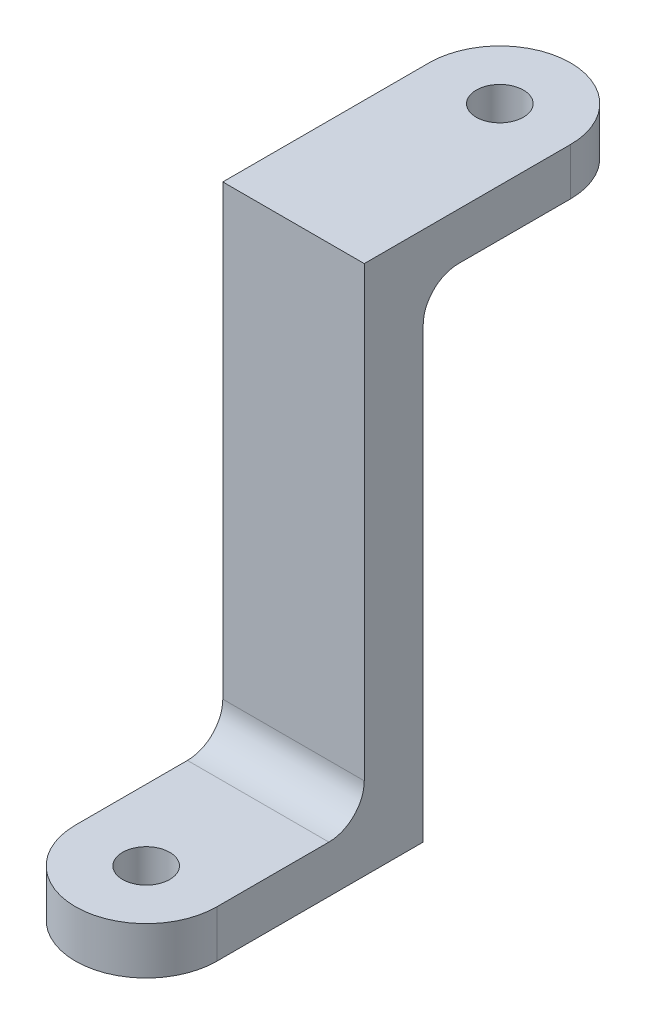
SolidWorks part; units mm, degrees
ref_plane "Front Plane" through (0, 0, 0) normal (0, 0, 1) x (1, 0, 0)
ref_plane "Top Plane" through (0, 0, 0) normal (0, 1, 0) x (1, 0, 0)
ref_plane "Right Plane" through (0, 0, 0) normal (1, 0, 0) x (0, 0, -1)
sketch "Sketch1" plane through (0, 0, 0) normal (0, 1, 0) x (1, 0, 0)
  line L0 (0, 30) -> (0, 0) construction
  line L1 (-6, 30) -> (-6, 0)
  line L2 (6, 30) -> (6, 0)
  circle A0 centre (0, 0) radius 2
  circle A1 centre (0, 30) radius 2
  circle A2 centre (0, 30) radius 6
  circle A3 centre (0, 0) radius 6
  point P11 (-6, 0)
  point P12 (6, 0)
  dimension "D1" = 4
  dimension "D2" = 4
  dimension "D3" = 4
  dimension "D4" = 4
  dimension "D5" = 30
extrude "Boss-Extrude1" add sketch "Sketch1" along normal blind 4
sketch "Sketch2" plane through (0, 4, 0) normal (0, 1, 0) x (1, 0, 0)
  line L0 (-6, 30) -> (6, 0) construction
  line L1 (-6, 30) -> (-6, 0) construction
  line L2 (6, 17.5) -> (-6, 17.5)
  line L3 (6, 17.5) -> (6, 12.5)
  line L4 (6, 12.5) -> (-6, 12.5)
  line L5 (-6, 17.5) -> (-6, 12.5)
  line L6 (6, 17.5) -> (-6, 12.5) construction
  line L7 (6, 12.5) -> (-6, 17.5) construction
  point P4 (0, 15)
  dimension "D1" = 5
extrude "Boss-Extrude2" add sketch "Sketch2" along normal blind 37 contours L3 L2 L5 L4
sketch "Sketch3" plane through (0, 41, 0) normal (0, 1, 0) x (1, 0, 0)
  line L3 (-6, 17.5) -> (6, 17.5)
  line L4 (-6, 12.5) -> (6, 12.5)
  line L5 (6, 12.5) -> (6, 17.5)
  line L6 (6, 17.5) -> (-6, 17.5)
  line L7 (-6, 17.5) -> (-6, 12.5)
  line L8 (-6, 12.5) -> (6, 12.5)
  line L9 (6, 12.5) -> (6, 17.5)
  line L10 (6, 17.5) -> (-6, 17.5)
  line L11 (-6, 17.5) -> (-6, 12.5)
  line L12 (6, 17.5) -> (6, 30)
  line L13 (-6, 30) -> (-6, 17.5)
  line L14 (-6, 17.5) -> (6, 17.5)
  line L15 (6, 17.5) -> (6, 30)
  line L16 (-6, 30) -> (-6, 17.5)
  circle A0 centre (0, 30) radius 2
  arc A1 (6, 30) -> (-6, 30) centre (0, 30) ccw
  arc A2 (6, 30) -> (-6, 30) centre (0, 30) ccw
  line M9 (-6, 12.5) -> (6, 12.5)
  line M10 (6, 12.5) -> (6, 17.5)
  line M11 (6, 17.5) -> (-6, 17.5)
  line M12 (-6, 17.5) -> (-6, 12.5)
  dimension "D3" = 4
  dimension "D1" = 0
  dimension "D2" = 0
extrude "Boss-Extrude3" add sketch "Sketch3" along normal blind 4 contours L15 A2 L16 A0 M11 | M12 M9 M10 M11
fillet "Fillet1" radius 3 3 edges at (0, 4, -17.5) (0, 41, -17.5) (0, 4, -12.5)
sketch "Sketch4" plane through (0, 4, 0) normal (0, 1, 0) x (1, 0, 0)
  line L1 (-6, 36.9207) -> (6, 36.9207)
  line L2 (-6, 36.9207) -> (-6, 17.5)
  line L3 (-6, 17.5) -> (6, 17.5)
  line L4 (6, 36.9207) -> (6, 17.5)
  point P5 (-6.9131, 36.9207)
  point P6 (0, 0)
  point P7 (-6, 17.5)
extrude "Cut-Extrude1" cut sketch "Sketch4" against normal up to next and the other way blind 10
